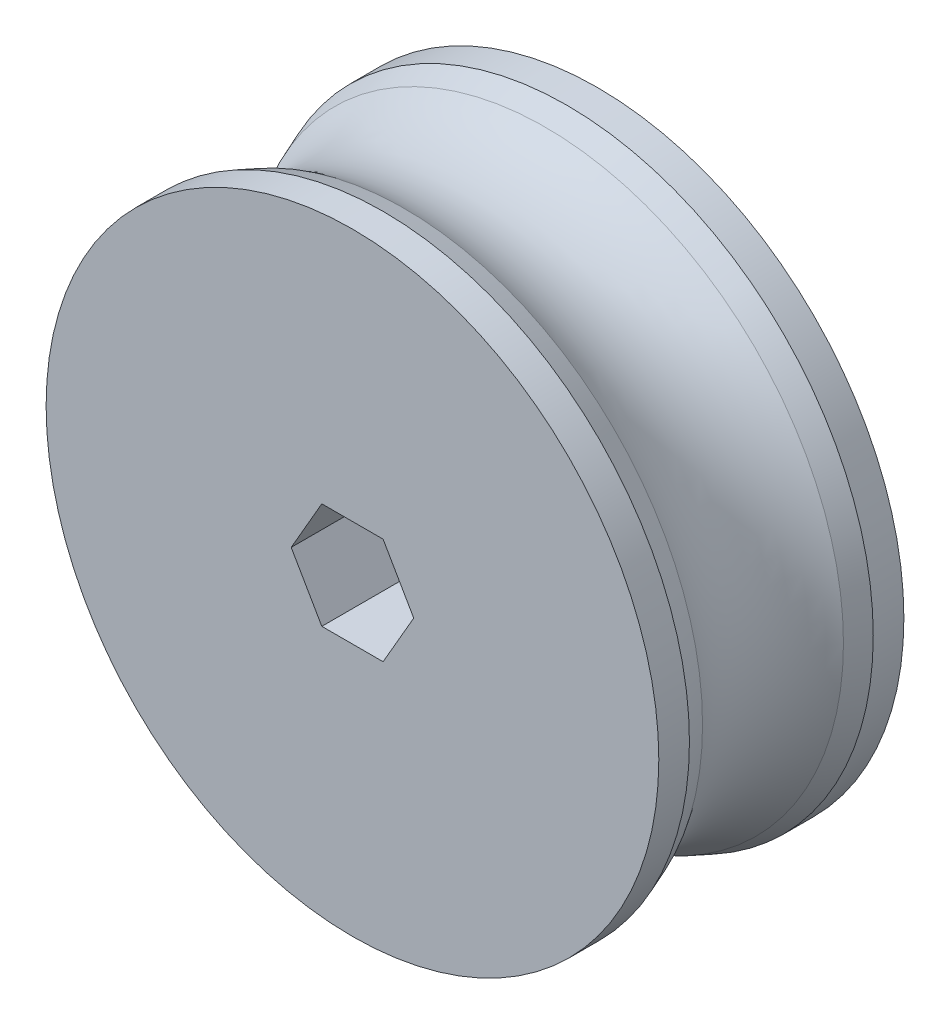
SolidWorks part; units mm, degrees
ref_plane "Front Plane" through (0, 0, 0) normal (0, 0, 1) x (1, 0, 0)
ref_plane "Top Plane" through (0, 0, 0) normal (0, 1, 0) x (1, 0, 0)
ref_plane "Right Plane" through (0, 0, 0) normal (1, 0, 0) x (0, 0, -1)
sketch "Sketch1" plane through (0, 0, 0) normal (0, 0, 1) x (1, 0, 0)
  circle A1 centre (0, 0) radius 25 construction
  circle A2 centre (0, 0) radius 25
extrude "Boss-Extrude1" add sketch "Sketch1" along normal blind 20
sketch "Sketch2" plane through (0, 0, 0) normal (1, 0, 0) x (0, 0, -1)
  line L0 (0, -25) -> (0, 25) construction
  line L1 (-20, 25) -> (-20, -25) construction
  line L2 (0, -25) -> (0, 25) construction
  line L3 (-20, 25) -> (-20, -25) construction
  line L4 (-20, 25) -> (0, 25) construction
  line L9 (-20, 25) -> (-17.5, 25) construction
  line L10 (-17.5, 25) -> (-15.75, 24.3185)
  line L11 (-10, 25) -> (-10, 32.5) construction
  line L12 (-2.5, 25) -> (-4.25, 24.3185)
  line L13 (0, 25) -> (-2.5, 25) construction
  line L14 (-17.5, 25) -> (-2.5, 25)
  circle A0 centre (-10, 32.5) radius 10 construction
  arc A1 (-15.75, 24.3185) -> (-4.25, 24.3185) centre (-10, 32.5) ccw
  point P4 (-10, 25)
  dimension "D1" = 20
  dimension "D2" = 7.5
  dimension "D3" = 2.5
  dimension "D4" = 1.75
ref_axis "Axis1" through (0, 0, 20) along (0, 0, -1)
revolve "Cut-Revolve1" cut sketch "Sketch2" angle 360 about axis through (0, 0, 20) along (0, 0, -1)
sketch "Sketch3" plane through (0, 0, 0) normal (0, 0, -1) x (-1, 0, 0)
  line L1 (5, 0) -> (2.5, 4.3301)
  line L2 (2.5, 4.3301) -> (-2.5, 4.3301)
  line L3 (-2.5, 4.3301) -> (-5, 0)
  line L4 (-5, 0) -> (-2.5, -4.3301)
  line L5 (-2.5, -4.3301) -> (2.5, -4.3301)
  line L6 (2.5, -4.3301) -> (5, 0)
  circle A0 centre (0, 0) radius 4.3301 construction
  circle A1 centre (0, 0) radius 5 construction
  dimension "D1" = 10
extrude "Cut-Extrude1" cut sketch "Sketch3" against normal through all
